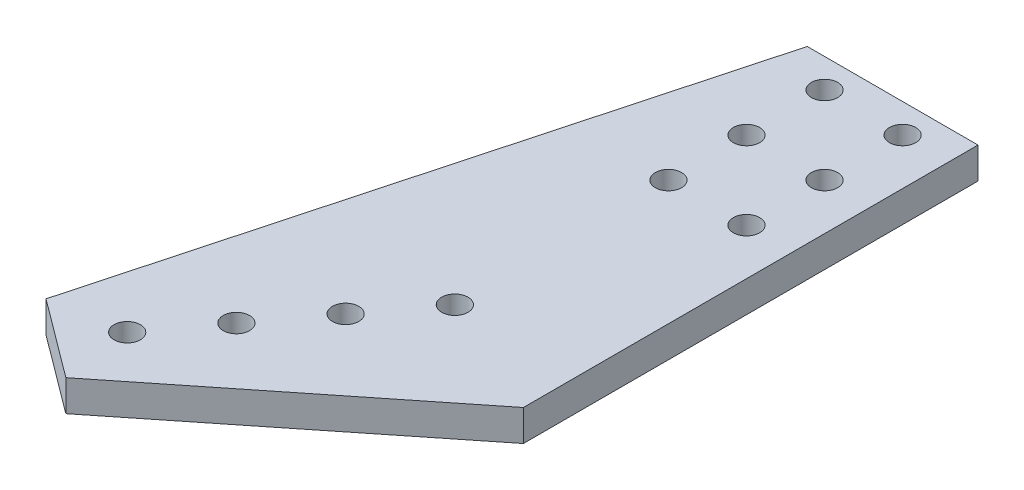
SolidWorks part; units mm, degrees
ref_plane "前视基准面" through (0, 0, 0) normal (0, 0, 1) x (1, 0, 0)
ref_plane "上视基准面" through (0, 0, 0) normal (0, 1, 0) x (1, 0, 0)
ref_plane "右视基准面" through (0, 0, 0) normal (1, 0, 0) x (0, 0, -1)
sketch "草图1" plane through (0, 0, 0) normal (0, 1, 0) x (1, 0, 0)
  line L0 (-80.1536, 59.7946) -> (86, 674)
  line L1 (86, 674) -> (261, 674)
  line L2 (261, 674) -> (261, 208)
  line L3 (261, 208) -> (0, 0)
  line L4 (-80.1536, 59.7946) -> (0, 0)
  line L5 (-40.0768, 29.8973) -> (-29937.3815, -40046.9186) construction
  line L6 (173.5, -326) -> (173.5, 49674) construction
  line L7 (-475.7, -554.048) -> (-326.5, -554.048) construction
  line L8 (-326.5, -554.048) -> (-326.5, -354.048) construction
  point P9 (-40.0768, 29.8973)
  point P13 (173.5, 674)
  dimension "D1" = 466
  dimension "D2" = 208
  dimension "D3" = 261
  dimension "D4" = 100
  dimension "D5" = 175
  dimension "D6" = 200
  dimension "D7" = 149.2
  dimension "D8" = 500
extrude "凸台-拉伸1" add sketch "草图1" along normal blind 32
sketch "草图2" plane through (0, 32, 0) normal (0, 1, 0) x (1, 0, 0)
  line L0 (173.5, -326) -> (173.5, 49674) construction
  line L1 (261, 674) -> (86, 674) construction
  line L2 (-40.0768, 29.8973) -> (29857.2279, 40106.7132) construction
  line L3 (-80.1536, 59.7946) -> (0, 0) construction
  line L4 (173.5, 316.1933) -> (261, 316.1933) construction
  line L5 (261, 208) -> (261, 674) construction
  circle A0 centre (133.5, 644.1933) radius 13.5
  circle A1 centre (213.5, 644.1933) radius 13.5
  circle A2 centre (133.5, 564.1933) radius 13.5
  circle A3 centre (213.5, 564.1933) radius 13.5
  circle A4 centre (133.5, 484.1933) radius 13.5
  circle A5 centre (213.5, 484.1933) radius 13.5
  circle A6 centre (134.6335, 264.0934) radius 13.5
  circle A7 centre (-8.8736, 71.7247) radius 13.5
  circle A8 centre (86.7978, 199.9705) radius 13.5
  circle A9 centre (38.9621, 135.8476) radius 13.5
  point P5 (173.5, 674)
  point P9 (-40.0768, 29.8973)
  dimension "D1" = 27
  dimension "D2" = 168
  dimension "D3" = 80
  dimension "D4" = 80
  dimension "D5" = 80
  dimension "D6" = 80
  dimension "D7" = 80
  dimension "D8" = 65
  dimension "D9" = 80
extrude "切除-拉伸1" cut sketch "草图2" against normal through all
